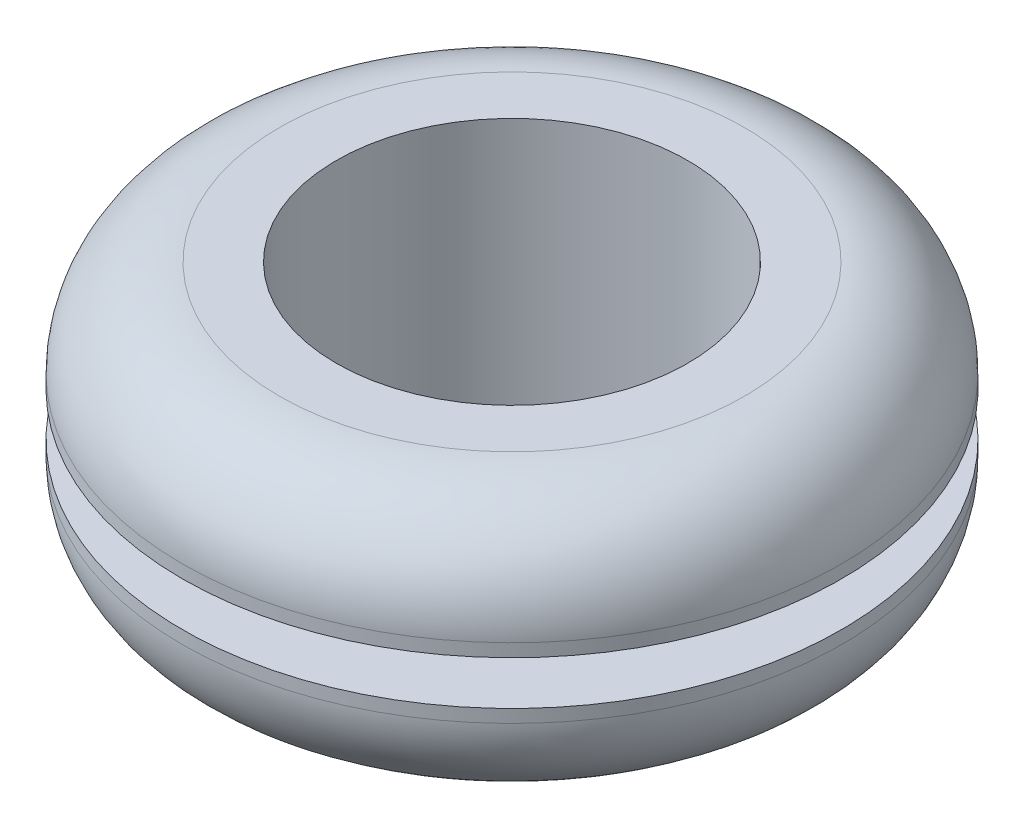
SolidWorks part; units mm, degrees
ref_plane "Front Plane" through (0, 0, 0) normal (0, 0, 1) x (1, 0, 0)
ref_plane "Top Plane" through (0, 0, 0) normal (0, 1, 0) x (1, 0, 0)
ref_plane "Right Plane" through (0, 0, 0) normal (1, 0, 0) x (0, 0, -1)
sketch "Sketch1" plane through (0, 0, 0) normal (0, 1, 0) x (1, 0, 0)
  circle A0 centre (0, 0) radius 8.7312
  dimension "D1" = 17.4625
extrude "Boss-Extrude1" add sketch "Sketch1" along normal blind 9.525
sketch "Sketch2" plane through (0, 9.525, 0) normal (0, 1, 0) x (1, 0, 0)
  circle A0 centre (0, 0) radius 6.35
  dimension "D1" = 12.7
sketch "Sketch3" plane through (0, 9.525, 0) normal (0, 1, 0) x (1, 0, 0)
  circle A0 centre (0, 0) radius 11.9062
  dimension "D1" = 23.8125
extrude "Boss-Extrude2" add sketch "Sketch3" against normal blind 3.9688
sketch "Sketch4" plane through (0, 0, 0) normal (0, -1, 0) x (-1, 0, 0)
  circle A0 centre (0, 0) radius 11.9062
  dimension "D1" = 23.8125
extrude "Boss-Extrude3" add sketch "Sketch4" against normal blind 3.9688
extrude "Cut-Extrude2" cut sketch "Sketch2" against normal through all
fillet "Fillet2" radius 3.5 2 edges at (0, 0, -11.9062) (0, 9.525, 11.9062)
